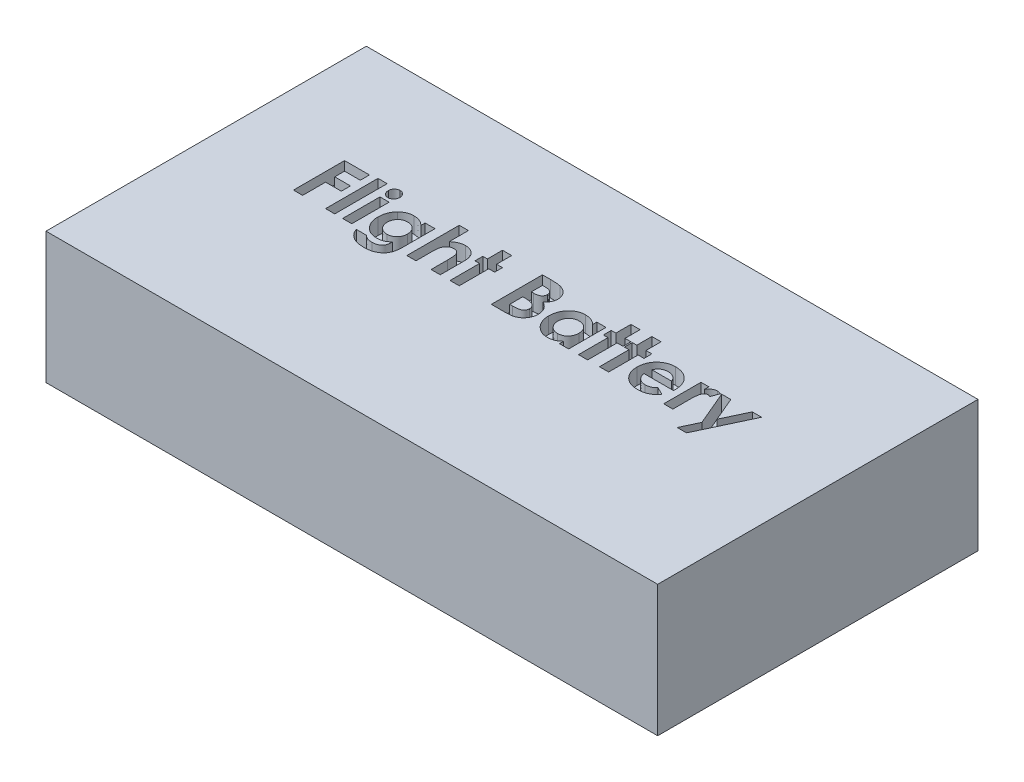
SolidWorks part; units mm, degrees
ref_plane "Front Plane" through (0, 0, 0) normal (0, 0, 1) x (1, 0, 0)
ref_plane "Top Plane" through (0, 0, 0) normal (0, 1, 0) x (1, 0, 0)
ref_plane "Right Plane" through (0, 0, 0) normal (1, 0, 0) x (0, 0, -1)
sketch "Sketch1" plane through (0, 0, 0) normal (0, 1, 0) x (1, 0, 0)
  line L1 (-18.6545, 9.6727) -> (19.3455, 9.6727)
  line L2 (-18.6545, 9.6727) -> (-18.6545, -10.2273)
  line L3 (-18.6545, -10.2273) -> (19.3455, -10.2273)
  line L4 (19.3455, 9.6727) -> (19.3455, -10.2273)
  dimension "D1" = 38
  dimension "D2" = 19.9
extrude "Boss-Extrude1" add sketch "Sketch1" along normal blind 8.15
ref_plane "Plane1" through (0, 8.15, 0) normal (0, 1, 0) x (1, 0, 0)
sketch "Sketch3" plane through (0, 8.15, 0) normal (0, 1, 0) x (1, 0, 0)
  text T0 "<b>Flight Battery</b>"
extrude "Cut-Extrude1" cut sketch "Sketch3" against normal blind 1
